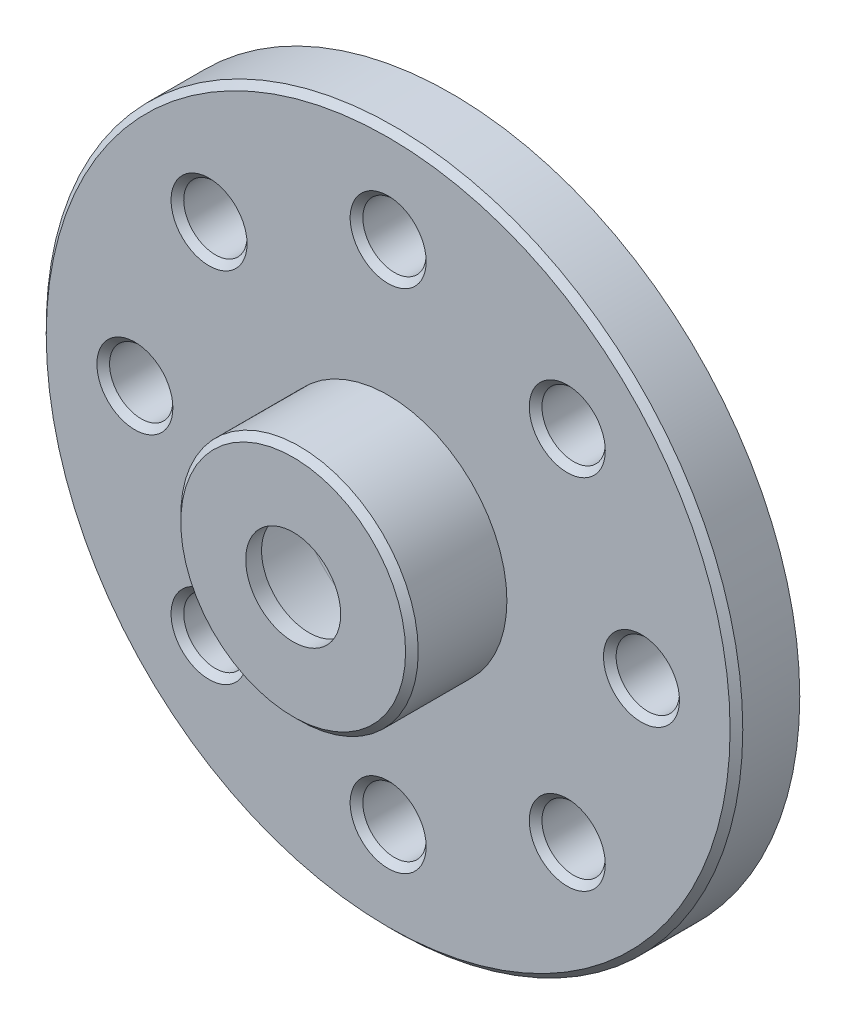
SolidWorks part; units mm, degrees
ref_plane "Front Plane" through (0, 0, 0) normal (0, 0, 1) x (1, 0, 0)
ref_plane "Top Plane" through (0, 0, 0) normal (0, 1, 0) x (1, 0, 0)
ref_plane "Right Plane" through (0, 0, 0) normal (1, 0, 0) x (0, 0, -1)
sketch "Sketch1" plane through (0, 0, 0) normal (0, 0, 1) x (1, 0, 0)
  circle A0 centre (0, 0) radius 11
  dimension "D1" = 22
extrude "Boss-Extrude2" add sketch "Sketch1" along normal blind 2
sketch "Sketch2" plane through (0, 0, 2) normal (0, 0, 1) x (1, 0, 0)
  circle A0 centre (0, 0) radius 3.75
  dimension "D1" = 7.5
extrude "Boss-Extrude3" add sketch "Sketch2" along normal blind 3 separate body
sketch "Sketch3" plane through (0, 0, 0) normal (0, 0, -1) x (-1, 0, 0)
  circle A0 centre (0, 0) radius 2.85
  dimension "D1" = 5.7
extrude "Cut-Extrude1" cut sketch "Sketch3" against normal blind 4.5
sketch "Sketch4" plane through (0, 0, 5) normal (0, 0, 1) x (1, 0, 0)
  circle A0 centre (0, 0) radius 1.5
extrude "Cut-Extrude2" cut sketch "Sketch4" against normal through all
sketch "Sketch6" plane through (0, 0, 2) normal (0, 0, 1) x (1, 0, 0)
  circle A0 centre (0, 8) radius 1
  dimension "D1" = 8
extrude "Cut-Extrude3" cut sketch "Sketch6" against normal through all
pattern_circular "CirPattern1" count 8 over 360 about axis through (0, 0, 0) along (0, 0, 1) of "Cut-Extrude3"
chamfer "Chamfer1" distance 0.2 angle 45 1 edges at (11, 0, 2)
chamfer "Chamfer2" distance 0.2 angle 45 1 edges at (3.75, 0, 5)
chamfer "Chamfer3" distance 0.2 angle 45 1 edges at (1, 8, 2)
chamfer "Chamfer4" distance 0.2 angle 45 2 edges at (8, -1, 2) (6.364, 4.9497, 2)
chamfer "Chamfer5" distance 0.2 angle 45 5 edges at (-4.9497, 6.364, 2) (-8, 1, 2) (-6.364, -4.9497, 2) (-1, -8, 2) (4.9497, -6.364, 2)
